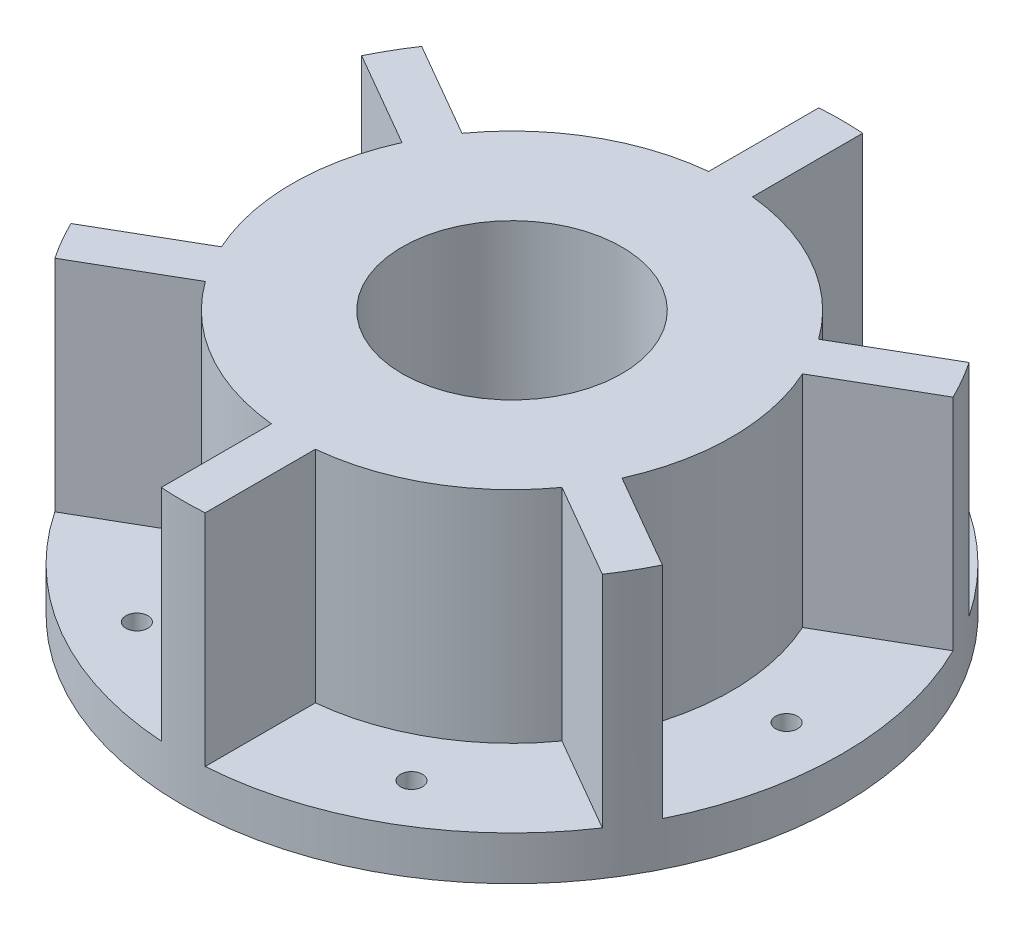
SolidWorks part; units mm, degrees
ref_plane "Front Plane" through (0, 0, 0) normal (0, 0, 1) x (1, 0, 0)
ref_plane "Top Plane" through (0, 0, 0) normal (0, 1, 0) x (1, 0, 0)
ref_plane "Right Plane" through (0, 0, 0) normal (1, 0, 0) x (0, 0, -1)
sketch "Sketch1" plane through (0, 0, 0) normal (0, 1, 0) x (1, 0, 0)
  circle A0 centre (0, 0) radius 75
  dimension "D1" = 150
extrude "Boss-Extrude1" add sketch "Sketch1" along normal blind 10
sketch "Sketch2" plane through (0, 10, 0) normal (0, 1, 0) x (1, 0, 0)
  circle A0 centre (0, 0) radius 50
  circle A1 centre (0, 0) radius 25
extrude "Boss-Extrude2" add sketch "Sketch2" along normal blind 50
sketch "Sketch3" plane through (0, 10, 0) normal (0, 1, 0) x (1, 0, 0)
  line L0 (3.0012, -49.9098) -> (4.5017, -74.8648) construction
  line L2 (-5, 74.8331) -> (-5, 49.7494)
  line L4 (5, 74.8331) -> (5, 49.7494)
  line L5 (-4.5017, 74.8648) -> (-3.0012, 49.9098) construction
  line L6 (-4.5017, -74.8648) -> (-3.0012, -49.9098) construction
  line L7 (3.0012, 49.9098) -> (4.5017, 74.8648) construction
  line L8 (5, -49.7494) -> (5, -74.8331)
  line L9 (-5, -49.7494) -> (-5, -74.8331)
  arc A0 (-5, -49.7494) -> (5, -49.7494) centre (0, 0) ccw
  arc A1 (-5, -74.8331) -> (5, -74.8331) centre (0, 0) ccw
  arc A2 (5, 74.8331) -> (-5, 74.8331) centre (0, 0) ccw
  arc A3 (5, 49.7494) -> (-5, 49.7494) centre (0, 0) ccw
  dimension "D1" = 10
extrude "Boss-Extrude4" add sketch "Sketch3" along normal blind 50
pattern_circular "CirPattern2" count 6 over 360 about axis through (0, 0, 0) along (0, 1, 0) of "Boss-Extrude4"
sketch "Sketch5" plane through (0, 10, 0) normal (0, 1, 0) x (1, 0, 0)
  circle A0 centre (0, 0) radius 62.5
  circle A1 centre (-62.5, 0) radius 2.5
  dimension "D1" = 125
extrude "Cut-Extrude5" cut sketch "Sketch5" against normal blind 5 contours A0 A1 | A0 A1
pattern_circular "CirPattern3" count 6 over 360 about axis through (0, 0, 0) along (0, 1, 0) of "Cut-Extrude5"
